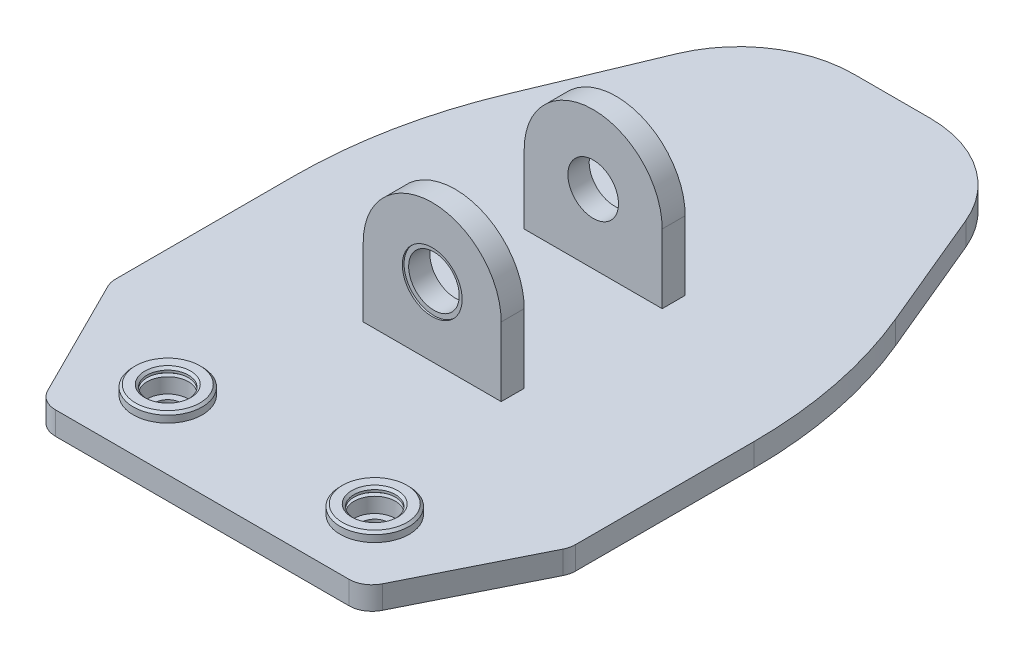
SolidWorks part; units mm, degrees
ref_plane "前视基准面" through (0, 0, 0) normal (0, 0, 1) x (1, 0, 0)
ref_plane "上视基准面" through (0, 0, 0) normal (0, 1, 0) x (1, 0, 0)
ref_plane "右视基准面" through (0, 0, 0) normal (1, 0, 0) x (0, 0, -1)
other "Configuration Table"
sketch "草图1" plane through (0, 0, 0) normal (0, 1, 0) x (1, 0, 0)
  line L0 (0, 0) -> (0, 255.8207) construction
  line L1 (-100, 0) -> (100, 0)
  line L2 (100, 0) -> (100, 180)
  line L3 (100, 180) -> (50, 300)
  line L4 (50, 300) -> (-50, 300)
  line L5 (-100, 180) -> (-50, 300)
  line L6 (-100, 0) -> (-100, 180)
  point P8 (0, 300)
  dimension "D1" = 300
  dimension "D2" = 100
  dimension "D3" = 120
  dimension "D4" = 50
extrude "凸台-拉伸1" add sketch "草图1" along normal blind 10
sketch "草图2" plane through (100, 0, 0) normal (1, 0, 0) x (0, 0, -1)
  line L0 (40, 100) -> (40, -10.3339) construction
  line L1 (0, 10) -> (0, 0) construction
  line L2 (0, 10) -> (0, 60)
  line L3 (80, 10) -> (80, 60)
  arc A0 (80, 60) -> (0, 60) centre (40, 60) ccw
  circle A1 centre (40, 60) radius 10
  line M6 (180, 10) -> (0, 10)
  dimension "D3" = 20
  dimension "D1" = 40
  dimension "D2" = 50
extrude "凸台-拉伸2" [suppressed] add sketch "草图2" against normal up to surface (200 mm away) contours A0 L0 A1 L3 M6 | L0 A0 L2 A1 M6
sketch "草图3" [suppressed] plane through (0, 10, 0) normal (0, 1, 0) x (1, 0, 0)
  line L0 (0, 0) -> (0, 135.8056) construction
  line L1 (-100, 0) -> (100, 0) construction
  line L2 (-70, 0) -> (70, 0)
  line L3 (-70, 0) -> (-70, 100)
  line L4 (-70, 100) -> (70, 100)
  line L5 (70, 0) -> (70, 100)
  line L6 (100, 0) -> (100, 80) construction
  line L7 (-100, 80) -> (-100, 0) construction
  dimension "D1" = 30
  dimension "D2" = 30
  dimension "D3" = 100
extrude "切除-拉伸1" [suppressed] cut sketch "草图3" along normal blind 171
sketch "草图4" plane through (0, 0, 0) normal (0, 0, 1) x (1, 0, 0)
  line L0 (0, 0) -> (0, 92.3322) construction
  line L1 (30, 40) -> (30, 10)
  line L2 (-30, 40) -> (-30, 10)
  line L3 (-100, 10) -> (100, 10) construction
  arc A0 (-30, 40) -> (30, 40) centre (0, 40) cw
  circle A1 centre (0, 40) radius 11
  line M10 (100, 10) -> (-100, 10)
  dimension "D2" = 30
  dimension "D3" = 22
  dimension "D1" = 30
extrude "凸台-拉伸3" add sketch "草图4" against normal blind 80 from offset 100 contours L0 L1 A0 A1 M10 | L0 A1 A0 L2 M10 offset against normal yes
sketch "草图5" plane through (0, 10, 0) normal (0, 1, 0) x (1, 0, 0)
  line L0 (-47.074, 140) -> (51.1394, 140) construction
  line L1 (30, 180) -> (-30, 180) construction
  line L2 (30, 100) -> (-30, 100) construction
  line L3 (-30, 100) -> (30, 100) construction
  line L4 (-40, 170) -> (40, 170)
  line L5 (-40, 170) -> (-40, 110)
  line L6 (-40, 110) -> (40, 110)
  line L7 (40, 170) -> (40, 110)
  line L8 (30, 180) -> (30, 100) construction
  line L9 (-30, 180) -> (-30, 100) construction
  dimension "D1" = 10
  dimension "D2" = 10
  dimension "D3" = 10
  dimension "D4" = 10
extrude "切除-拉伸2" cut sketch "草图5" along normal blind 110 contours L7 L6 L5 L4
fillet "圆角1" radius 50 2 edges at (-50, 5, -300) (50, 5, -300)
fillet "圆角2" radius 200 2 edges at (-100, 5, -180) (100, 5, -180)
sketch "草图6" [suppressed] plane through (100, 0, 0) normal (1, 0, 0) x (0, 0, -1)
  line L0 (40, 60) -> (40, -52.2503) construction
  circle A0 centre (40, 60) radius 10 construction
  circle A1 centre (40, 60) radius 10 construction
  arc A2 (73.0468, 82.5368) -> (6.9532, 82.5368) centre (40, -25) ccw
  arc A3 (80, 60) -> (0, 60) centre (40, 60) ccw construction
  arc A4 (73.0468, 82.5368) -> (6.9532, 82.5368) centre (40, 60) ccw
  dimension "D2" = 225
  dimension "D1" = 25
extrude "切除-拉伸3" [suppressed] cut sketch "草图6" against normal through all both and the other way through all contours A2 A4
sketch "草图7" plane through (0, 10, 0) normal (0, 1, 0) x (1, 0, 0)
  line L0 (0, 0) -> (0, 141.3983) construction
  line L1 (-100, 0) -> (100, 0) construction
  circle A0 centre (45, 30) radius 9
  dimension "D1" = 18
  dimension "D2" = 45
  dimension "D3" = 30
extrude "切除-拉伸6" cut sketch "草图7" against normal offset from surface (6 mm away) 4 contours A0 up to face at (0, 0, -186.7805)
sketch "草图10" plane through (0, 4, 0) normal (0, 1, 0) x (1, 0, 0)
  circle A0 centre (45, 30) radius 6
  dimension "D1" = 12
extrude "切除-拉伸7" cut sketch "草图10" against normal blind 28 contours A0
sketch "草图11" plane through (0, 10, 0) normal (0, 1, 0) x (1, 0, 0)
  circle A0 centre (45, 30) radius 12.5
  circle A1 centre (45, 30) radius 16.5
  dimension "D1" = 25
  dimension "D2" = 33
extrude "切除-拉伸8" [suppressed] cut sketch "草图11" against normal blind 5
sketch "草图12" plane through (0, 10, 0) normal (0, 1, 0) x (1, 0, 0)
  circle A0 centre (45, 30) radius 15
  dimension "D1" = 30
extrude "凸台-拉伸5" add sketch "草图12" along normal blind 4 contours A0
sketch "草图13" plane through (0, 14, 0) normal (0, 1, 0) x (1, 0, 0)
  circle A0 centre (45, 30) radius 9
  dimension "D1" = 18
extrude "切除-拉伸9" cut sketch "草图13" against normal blind 4
sketch "草图14" plane through (0, 14, 0) normal (0, 1, 0) x (1, 0, 0)
  circle A0 centre (45, 30) radius 11
  circle A1 centre (45, 30) radius 9 construction
  circle A2 centre (45, 30) radius 9 construction
  circle A3 centre (45, 30) radius 9
  dimension "D1" = 2
extrude "卡簧槽" cut sketch "草图14" against normal blind 1.5 from offset 2 contours A0 offset against normal yes
chamfer "倒角1" distance 1 angle 45 2 edges at (45, 14, -15) (45, 14, -21)
ref_plane "基准面1" through (0, 0, 0) normal (-1, 0, 0) x (0, 0, 1)
mirror "镜向1" about plane through (0, 0, 0) normal (-1, 0, 0) of "切除-拉伸6", "切除-拉伸7", "凸台-拉伸5", "切除-拉伸9", "卡簧槽", "倒角1"
sketch "草图16" plane through (0, 0, -100) normal (0, 0, 1) x (1, 0, 0)
  circle A0 centre (0, 40) radius 13
  dimension "D1" = 26
extrude "切除-拉伸10" cut sketch "草图16" against normal blind 0.75
sketch "草图17" plane through (0, 0, -180) normal (0, 0, -1) x (-1, 0, 0)
  circle A0 centre (0, 40) radius 13
  dimension "D1" = 26
extrude "切除-拉伸11" cut sketch "草图17" against normal blind 0.75 contours A0
sketch "草图18" plane through (-100, 0, 0) normal (-1, 0, 0) x (0, 0, 1)
  line L0 (-30, 92.2697) -> (-30, -20.0308) construction
  line L1 (-40, 10) -> (-40, 30)
  line L2 (-140, 10) -> (0, 10) construction
  line L3 (-20, 30) -> (-20, 10)
  line L4 (-40, 10) -> (-20, 10)
  arc A0 (-20, 30) -> (-40, 30) centre (-30, 30) ccw
  circle A1 centre (-30, 30) radius 2.5
  dimension "D2" = 5
  dimension "D4" = 10
  dimension "D1" = 30
  dimension "D3" = 20
extrude "凸台-拉伸6" [suppressed] add sketch "草图18" against normal up to surface (200 mm away) contours A1 L0 | L0 A1 | L3 L4 L1 A0
sketch "草图20" plane through (0, 10, 0) normal (0, 1, 0) x (1, 0, 0)
  line L0 (0, 0) -> (0, 309.5578) construction
  line L1 (-100, 0) -> (100, 0) construction
  line L2 (-60.0864, 49.2403) -> (-60.0864, 11.6041)
  line L3 (75.0864, 51.8093) -> (107.8414, 51.8093)
  line L4 (75.0864, 51.8093) -> (75.0864, 7.1083)
  line L5 (75.0864, 7.1083) -> (107.8414, 7.1083)
  line L6 (107.8414, 51.8093) -> (107.8414, 7.1083)
  line L7 (15, 49.2403) -> (60.0864, 49.2403)
  line L8 (15, 49.2403) -> (15, 11.6041)
  line L9 (15, 11.6041) -> (60.0864, 11.6041)
  line L10 (60.0864, 49.2403) -> (60.0864, 11.6041)
  line L11 (-15, 11.6041) -> (-60.0864, 11.6041)
  line L12 (-15, 49.2403) -> (-15, 11.6041)
  line L13 (-15, 49.2403) -> (-60.0864, 49.2403)
  line L14 (-107.8414, 51.8093) -> (-107.8414, 7.1083)
  line L15 (-75.0864, 7.1083) -> (-107.8414, 7.1083)
  line L16 (-75.0864, 51.8093) -> (-75.0864, 7.1083)
  line L17 (-75.0864, 51.8093) -> (-107.8414, 51.8093)
  dimension "D1" = 15
  dimension "D2" = 15
extrude "切除-拉伸12" [suppressed] cut sketch "草图20" along normal through all
chamfer "倒角2" distance 30 distance2 60 1 edges at (100, 5, 0)
chamfer "倒角3" distance 60 distance2 30 1 edges at (-100, 5, 0)
fillet "圆角3" radius 10 4 edges at (-70, 5, 0) (-100, 5, -60) (70, 5, 0) (100, 5, -60)
